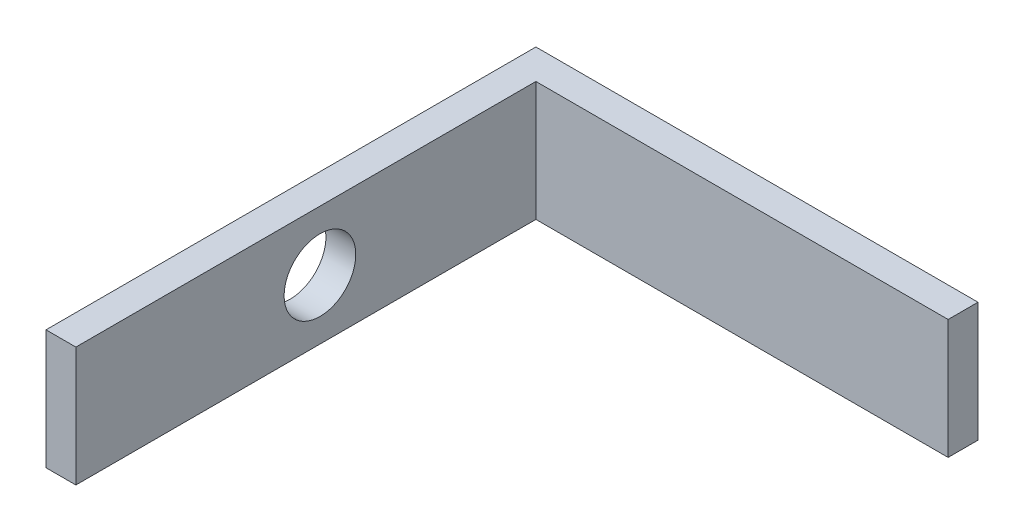
SolidWorks part; units mm, degrees
ref_plane "Front Plane" through (0, 0, 0) normal (0, 0, 1) x (1, 0, 0)
ref_plane "Top Plane" through (0, 0, 0) normal (0, 1, 0) x (1, 0, 0)
ref_plane "Right Plane" through (0, 0, 0) normal (1, 0, 0) x (0, 0, -1)
sketch "Sketch1" plane through (0, 0, 0) normal (0, 1, 0) x (1, 0, 0)
  line L1 (-2.7577, -19.8611) -> (1.211, -19.8611)
  line L2 (-2.7577, -19.8611) -> (-2.7577, 45.2264)
  line L3 (-2.7577, 45.2264) -> (6.2797, 45.2264)
  line L4 (1.211, -19.8611) -> (1.211, 41.2577)
  line L5 (-2.7577, -19.8611) -> (6.2797, 45.2264) construction
  line L6 (-2.7577, 45.2264) -> (1.211, -19.8611) construction
  line L7 (6.2797, 45.2264) -> (55.9798, 45.2264)
  line L9 (1.211, 41.2577) -> (55.9798, 41.2577)
  line L10 (55.9798, 45.2264) -> (55.9798, 41.2577)
  point P0 (0, 0)
  dimension "D1" = 3.9688
  dimension "D2" = 3.9688
  dimension "D3" = 54.7687
  dimension "D4" = 61.1187
extrude "Boss-Extrude1" add sketch "Sketch1" along normal mid plane 15.875
sketch "Sketch3" plane through (-2.7577, 0, 0) normal (-1, 0, 0) x (0, 0, 1)
  circle A0 centre (-12.5666, 0) radius 4.7625
  dimension "D1" = 9.525
extrude "Cut-Extrude1" cut sketch "Sketch3" against normal up to surface (3.9688 mm away) up to face at (1.211, 0, -10.6983)
